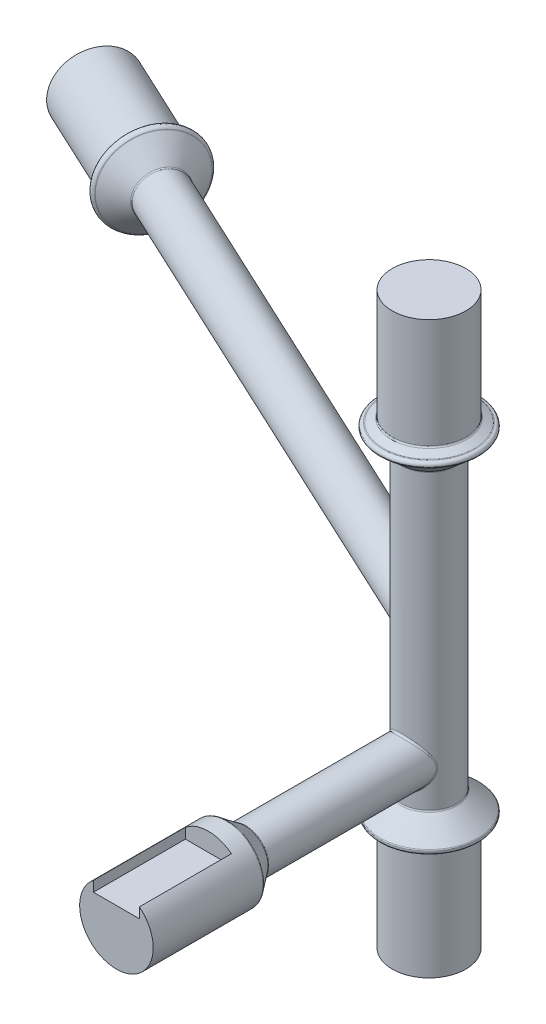
SolidWorks part; units mm, degrees
ref_plane "Front Plane" through (0, 0, 0) normal (0, 0, 1) x (1, 0, 0)
ref_plane "Top Plane" through (0, 0, 0) normal (0, 1, 0) x (1, 0, 0)
ref_plane "Right Plane" through (0, 0, 0) normal (1, 0, 0) x (0, 0, -1)
sketch "Sketch3" plane through (0, 0, 0) normal (0, 0, 1) x (1, 0, 0)
  line L1 (0, 31) -> (4, 31)
  line L2 (4, 31) -> (4, 19)
  line L3 (4, 19) -> (5, 18.5)
  line L9 (0, 31) -> (0, -31) construction
  line L10 (5.3653, 18) -> (3, 16)
  line L11 (3, 16) -> (3, 0)
  line L12 (3, 0) -> (0, 0)
  line L13 (3, -16) -> (3, 0)
  line L14 (5.3653, -18) -> (3, -16)
  line L15 (4, -19) -> (5, -18.5)
  line L16 (4, -31) -> (4, -19)
  line L17 (0, -31) -> (4, -31)
  arc A0 (5, 18.5) -> (5.3653, 18) centre (5.0548, 18.1566) cw
  arc A1 (5, -18.5) -> (5.3653, -18) centre (5.0548, -18.1566) ccw
  point P5 (4, 25)
  point P18 (4, -25)
  dimension "D1" = 4
  dimension "D2" = 25
  dimension "D3" = 12
  dimension "D4" = 0.5
  dimension "D5" = 16
  dimension "D6" = 2
  dimension "D7" = 2.3653
  dimension "D8" = 3
revolve "Revolve3" add sketch "Sketch3" angle 360 about L9
sketch "Sketch5" plane through (0, 0, 0) normal (0, 0, 1) x (1, 0, 0)
  line L7 (0, -9.5) -> (0, -14.5) construction
  circle A0 centre (0, -12) radius 2.5
extrude "Boss-Extrude3" add sketch "Sketch5" along normal blind 20
sketch "Sketch7" plane through (0, 0, 20) normal (0, 0, 1) x (1, 0, 0)
  circle A0 centre (0, -12) radius 4
  dimension "D1" = 8
extrude "Boss-Extrude4" add sketch "Sketch7" along normal blind 14
sketch "Sketch8" plane through (0, 0, 0) normal (1, 0, 0) x (0, 0, -1)
  line L0 (-20, -9.5) -> (-22, -8)
  line L1 (-20, -8) -> (-34, -8) construction
  line L2 (-22, -8) -> (-20, -8)
  line L3 (-20, -16) -> (-20, -8) construction
  line L4 (-20, -8) -> (-20, -9.5)
  line L5 (-34, -12) -> (-20, -12) construction
  dimension "D1" = 2
revolve "Cut-Revolve1" cut sketch "Sketch8" angle 360 about L5
ref_plane "Plane1" through (0, -8, 0) normal (0, 1, 0) x (1, 0, 0)
sketch "Sketch9" plane through (0, -8, 0) normal (0, 1, 0) x (1, 0, 0)
  line L0 (0, -200034) -> (0, 199980) construction
  line L1 (2.5, -24) -> (-2.5, -24)
  line L2 (2.5, -24) -> (2.5, -34)
  line L3 (2.5, -34) -> (-2.5, -34)
  line L4 (-2.5, -24) -> (-2.5, -34)
  line L5 (2.5, -24) -> (-2.5, -34) construction
  line L6 (2.5, -34) -> (-2.5, -24) construction
  line L7 (-4, -34) -> (4, -34) construction
  point P0 (0, -29)
  dimension "D1" = 5
  dimension "D2" = 10
extrude "Cut-Extrude1" cut sketch "Sketch9" against normal blind 2
sketch "Sketch10" plane through (0, 0, 0) normal (0, 1, 0) x (1, 0, 0)
  line L7 (0, 0) -> (0, 41.7981) construction
  line L11 (-67.9731, 31.6964) -> (-54.3785, 25.3571)
  line L12 (-69.6636, 28.0711) -> (-67.9731, 31.6964)
  line L13 (-58.7879, 22.9997) -> (-69.6636, 28.0711)
  line L14 (-58.7879, 22.9997) -> (-58.8406, 22.0011)
  line L15 (-55.435, 23.0913) -> (-58.165, 21.831)
  line L16 (-1.0565, -2.2658) -> (0, 0)
  line L17 (-55.435, 23.0913) -> (-1.0565, -2.2658)
  line L18 (0, 0) -> (-54.3785, 25.3571)
  arc A1 (-58.165, 21.831) -> (-58.8406, 22.0011) centre (-58.4369, 22.1778) cw
revolve "Revolve4" add sketch "Sketch10" angle 360 about L18
fillet "Fillet1" radius 0.2 16 edges at (-4, 19, 0) (-5, 18.5, 0) (-5.3653, 18, 0) (-55.4069, 0, -30.2502) (-54.6758, 0, -30.9324) (-54.1113, 0, -30.5243) (-53.3219, 0, -27.6229) (-5.3653, -18, 0) (-5, -18.5, 0) (-4, -19, 0) (4, -12, 22) (2.5, -12, 20) (-3, 16, 0) (-1.8854, 2.1243, -2.3335) (2.4698, -12.3876, 1.703) (-3, -16, 0)
